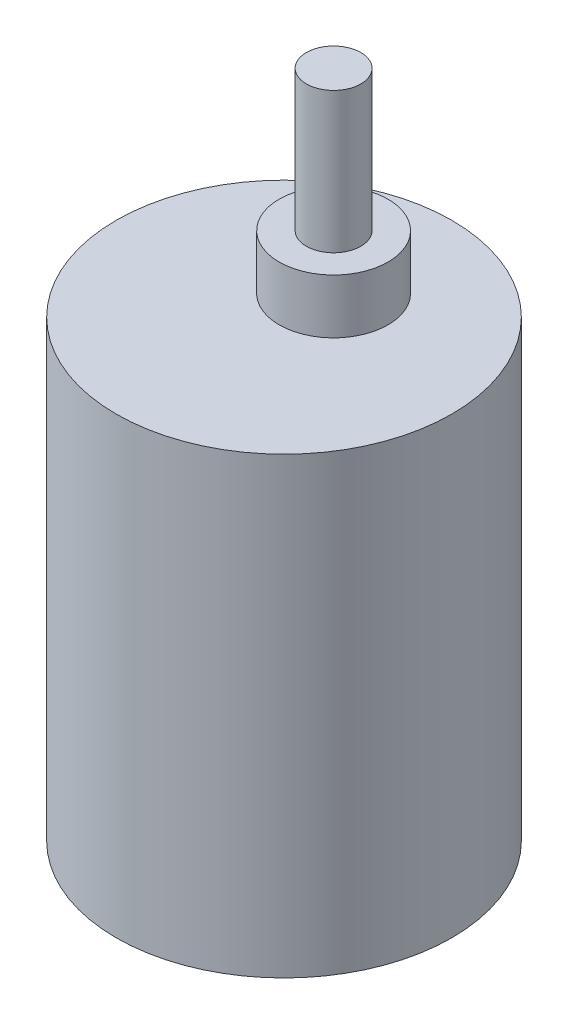
SolidWorks part; units mm, degrees
ref_plane "前视" through (0, 0, 0) normal (0, 0, 1) x (1, 0, 0)
ref_plane "上视" through (0, 0, 0) normal (0, 1, 0) x (1, 0, 0)
ref_plane "右视" through (0, 0, 0) normal (1, 0, 0) x (0, 0, -1)
sketch "Sketch1" plane through (0, 0, 0) normal (0, 1, 0) x (1, 0, 0)
  circle A0 centre (0, 0) radius 18.5
extrude "Extrude1" add sketch "Sketch1" along normal blind 50
sketch "Sketch2" plane through (0, 50, 0) normal (0, 1, 0) x (1, 0, 0)
  circle A0 centre (0.4675, 5) radius 6
  dimension "D1" = 5
extrude "Extrude2" add sketch "Sketch2" along normal blind 6
sketch "Sketch3" plane through (0, 56, 0) normal (0, 1, 0) x (1, 0, 0)
  circle A0 centre (0.4675, 5) radius 3
extrude "Extrude3" add sketch "Sketch3" along normal blind 15.5
